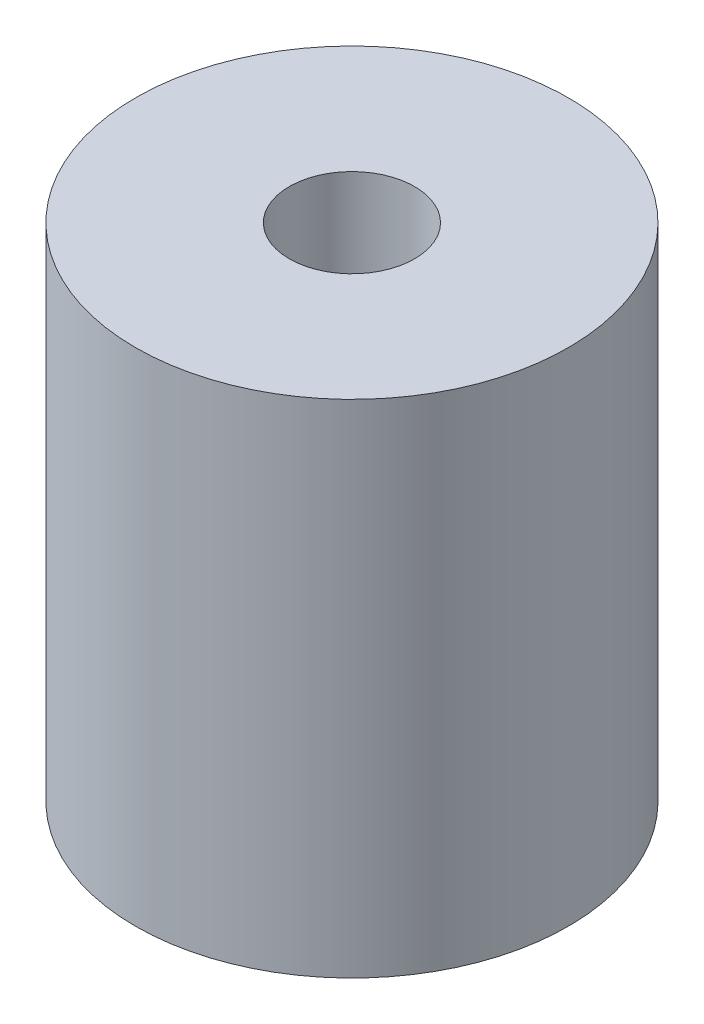
SolidWorks part; units mm, degrees
ref_plane "Plano frontal" through (0, 0, 0) normal (0, 0, 1) x (1, 0, 0)
ref_plane "Plano superior" through (0, 0, 0) normal (0, 1, 0) x (1, 0, 0)
ref_plane "Plano direito" through (0, 0, 0) normal (1, 0, 0) x (0, 0, -1)
sketch "Esboço1" plane through (0, 0, 0) normal (0, 1, 0) x (1, 0, 0)
  circle A0 centre (0, 0) radius 3.25
  circle A1 centre (0, 0) radius 9.5
  circle A2 centre (0, 0) radius 2.75
  dimension "D1" = 6.5
  dimension "D2" = 19
  dimension "D3" = 5.5
extrude "Ressalto-extrusão1" add sketch "Esboço1" along normal mid plane 22 contours A1 A0 | A0 A2
